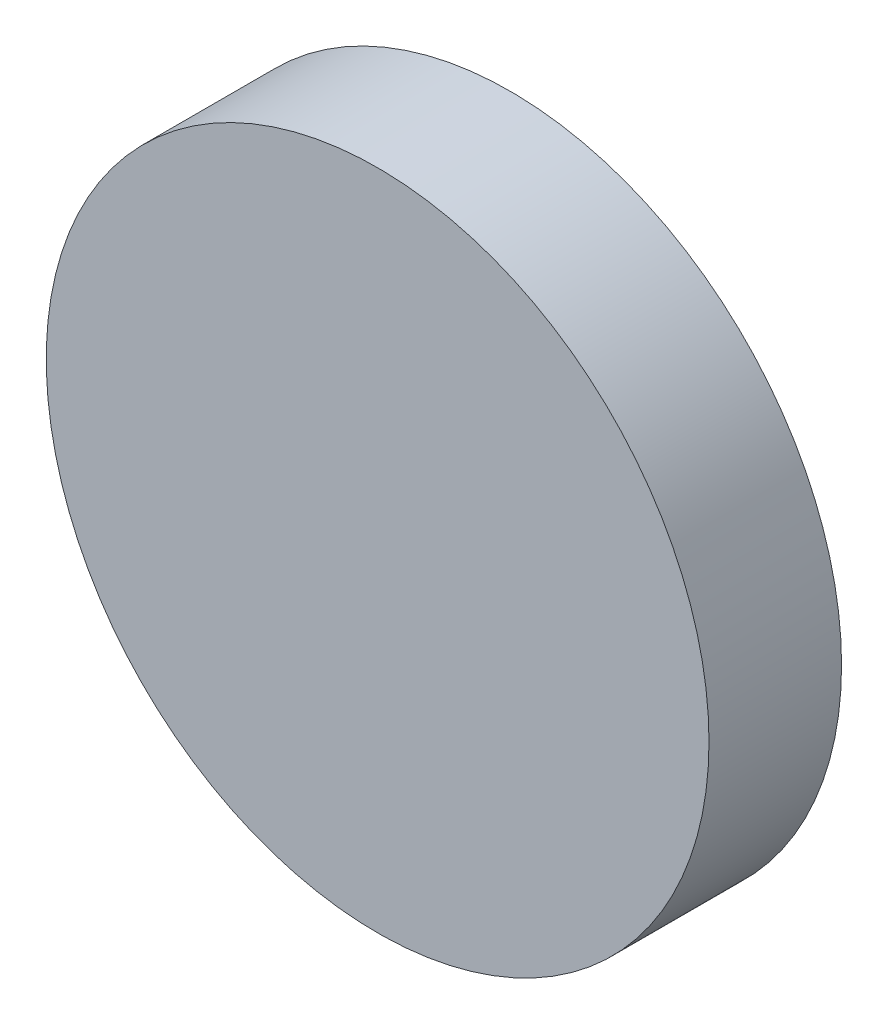
SolidWorks part; units mm, degrees
ref_plane "Front Plane" through (0, 0, 0) normal (1, 0, 0) x (0, 1, 0)
ref_plane "Top Plane" through (0, 0, 0) normal (0, 0, 1) x (0, 1, 0)
ref_plane "Right Plane" through (0, 0, 0) normal (0, 1, 0) x (-1, 0, 0)
sketch "Sketch1" plane through (0, 0, 0) normal (0, 0, 1) x (0, 1, 0)
  circle A0 centre (0, 0) radius 15
  dimension "D1" = 30
extrude "Boss-Extrude1" add sketch "Sketch1" along normal blind 6
